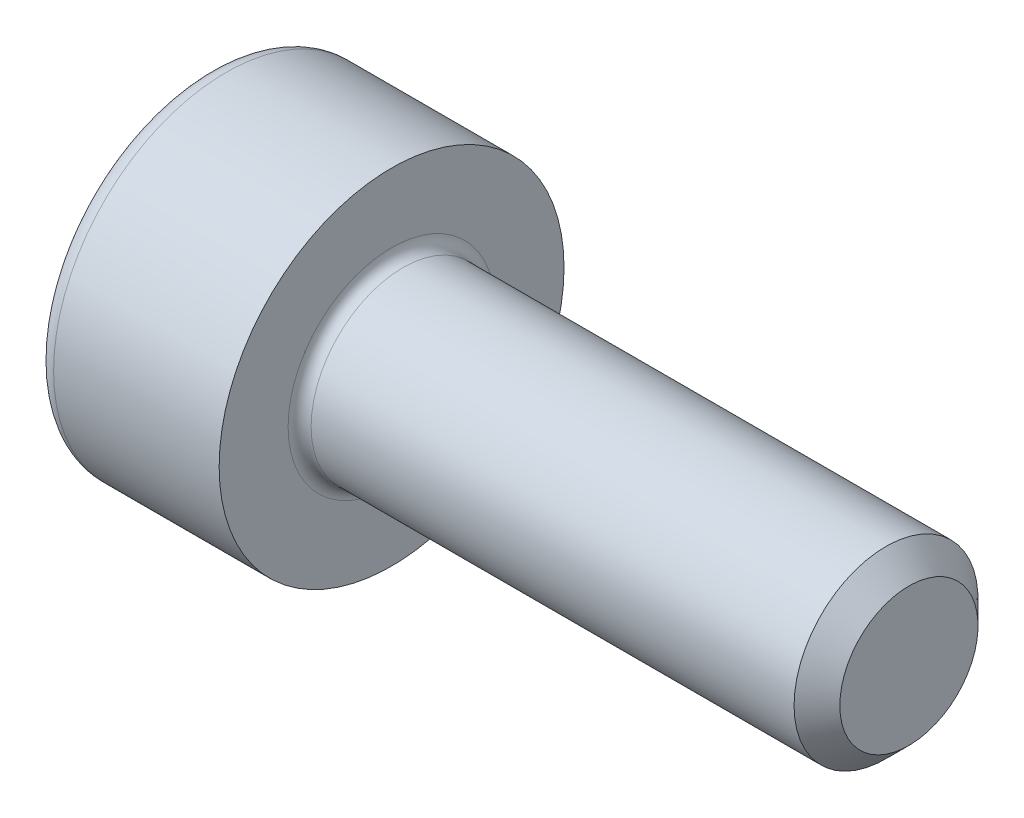
SolidWorks part; units mm, degrees
revolve "Base-Revolve" add sketch "BodySke"
sketch "BodySke" plane through (0, 0, 0) normal (0, 0, 1) x (1, 0, 0)
  line L0 (0, 0) -> (0, 1.5)
  line L1 (0, 1.5) -> (1.6, 1.5)
  line L2 (1.6, 1.5) -> (1.6, 0.8)
  line L3 (1.6, 0.8) -> (5.901, 0.8)
  line L4 (6.1, 0.601) -> (6.1, 0)
  line L5 (6.1, 0) -> (0, 0)
  line L6 (-31.75, 0) -> (127, 0) construction
  line L8 (6.1, 0.601) -> (5.901, 0.8)
  line L10 (6.1, -0.601) -> (5.901, -0.8) construction
  line L11 (1.95, 9.525) -> (1.95, 3.175) construction
  line L12 (1.6, 9.525) -> (1.6, 3.175) construction
  line L13 (-53.9, 9.525) -> (-53.9, 3.175) construction
  dimension "Head_ht" = 1.6
  dimension "Length" = 4.5
  dimension "Body_ch_ang" = 45
  dimension "Diameter" = 1.6
  dimension "Minor_dia" = 1.202
  dimension "Advance" = 0.35
  dimension "Thread_nom" = 4.5
  dimension "Thread_length" = 60
  dimension "Head_dia" = 3
cosmetic thread "ThreadCosmetic" [suppressed]
fillet "Fillet1" radius 0.1 1 edges at (1.6, 0, 0.8)
fillet "Fillet2" radius 0.16 1 edges at (0, 0, 1.5)
ref_plane "Plane1" through (0, 0, 0) normal (0, 0, 1) x (1, 0, 0)
ref_plane "Plane2" through (0, 0, 0) normal (0, 1, 0) x (1, 0, 0)
ref_plane "Plane3" through (0, 0, 0) normal (1, 0, 0) x (0, 0, -1)
sketch "Sketch2" plane through (0, 0, 0) normal (0, 0, 1) x (1, 0, 0)
  line L0 (0, 0.76) -> (0.7, 0.76)
  line L1 (0.7, 0.76) -> (1.1388, 0)
  line L2 (-31.75, 0) -> (127, 0) construction
  line L3 (1.1388, 0) -> (0, 0)
  line L4 (0, 0) -> (0, 0.76)
  line L6 (0, 0) -> (47.625, 0) construction
  dimension "D1" = 0.76
  dimension "D2" = 60
  dimension "Depth" = 0.7
revolve "Hex-PreBroach" cut sketch "Sketch2" angle 360 about L6
sketch "Sketch3" plane through (0, 0, 0) normal (-1, 0, 0) x (0, 0.5, 0.866)
  line L0 (0.4388, 0.76) -> (-0.4388, 0.76)
  line L1 (-0.4388, 0.76) -> (-0.8776, 0)
  line L2 (0.4388, 0.76) -> (0.8776, 0)
  line L3 (0.4388, -0.76) -> (0.8776, 0)
  line L4 (0.4388, -0.76) -> (-0.4388, -0.76)
  line L5 (-0.4388, -0.76) -> (-0.8776, 0)
  dimension "D1" = 0.76
  dimension "D2" = 0.76
  dimension "Hex_size" = 1.52
extrude "Hex" cut sketch "Sketch3" against normal blind 0.7
sketch "ThdSchSke" plane through (0, 0, 0) normal (0, 0, 1) x (1, 0, 0)
  line L0 (2.65, -0.601) -> (2.5107, -0.8)
  line L1 (2.65, -0.601) -> (2.7893, -0.8)
  line L2 (2.7893, -0.8) -> (2.7893, -1)
  line L3 (-3.175, 0) -> (5.1513, 0) construction
  line L4 (0, 1.34) -> (0, -1.34) construction
  line L5 (2.7893, -1) -> (2.5107, -1)
  line L6 (2.5107, -1) -> (2.5107, -0.8)
  dimension "Thread_minor" = 1.202
  dimension "Diameter" = 1.6
  dimension "Start" = 2.65
revolve "ThreadSchematic" [suppressed] cut sketch "ThdSchSke" angle 360 about L3
pattern_linear "ThdSchPat" [suppressed]
equation "\"D2@Sketch3\" = \"Hex_size@Sketch3\" / 2"
equation "\"D1@Sketch3\" = \"Hex_size@Sketch3\" / 2"
equation "\"D1@Sketch2\" = \"Hex_size@Sketch3\" / 2"
equation "\"Thread_minor@ThreadCosmetic\"  =  \"Minor_dia@BodySke\""
equation "\"Depth@Sketch2\" =  \"Key_eng@Hex\""
equation "\"Thread_length@ThreadCosmetic\" = ((sgn( (\"Length@BodySke\" - \"Advance@BodySke\" * 3.0) - \"Thread_nom@BodySke\" )-1)*( (\"Length@BodySke\" - \"Advance@BodySke\" * 3.0) - \"Thread_nom@BodySke\" ))/-2+ \"Thread_nom@BodySke\""
equation "\"Thread_minor@ThdSchSke\" = \"Minor_dia@BodySke\""
equation "\"Diameter@ThdSchSke\" = \"Diameter@BodySke\""
equation "\"Overcut@ThdSchSke\" = \"Diameter@BodySke\" * 1.25"
equation "\"Start@ThdSchSke\" = \"Head_ht@BodySke\" + \"Length@BodySke\" - \"Thread_length@ThreadCosmetic\"  '---Non-countersunk---"
equation "\"Num_threads@ThdSchPat\" = int( \"Thread_length@ThreadCosmetic\" / \"Advance@BodySke\" + 0.999 )  + 1"
equation "\"Advance@ThdSchPat\" = \"Thread_length@ThreadCosmetic\" /  (\"Num_threads@ThdSchPat\" - 1) 'relax it"
equation "\"Num_threads@ThdSchPat\" = \"Num_threads@ThdSchPat\" - sgn( \"Num_threads@ThdSchPat\" - 1) '---chamfered tips only---"
